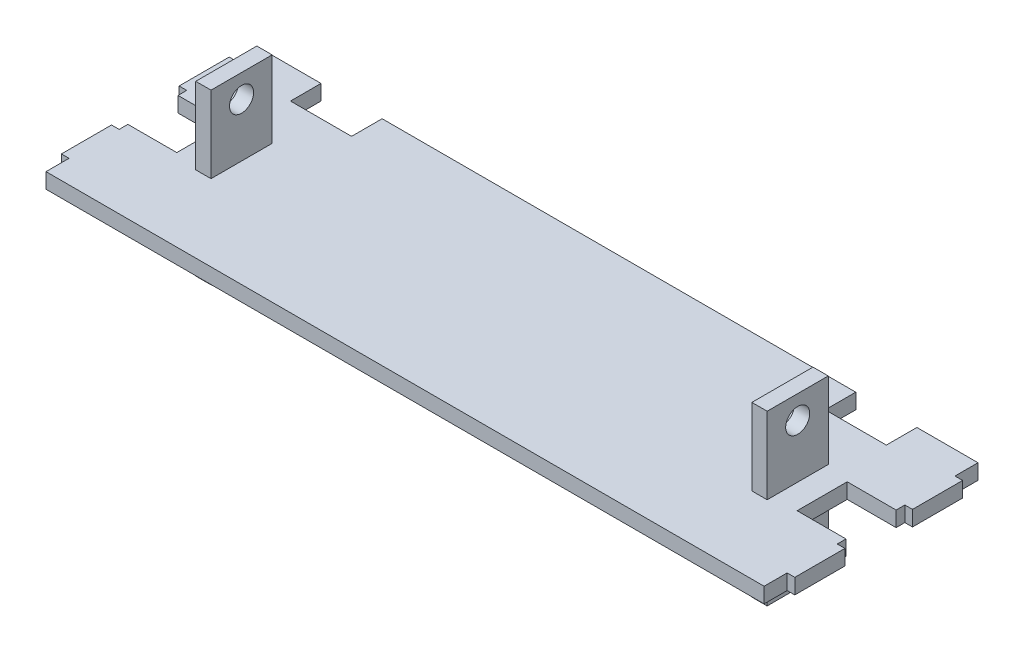
SolidWorks part; units mm, degrees
ref_plane "Front Plane" through (0, 0, 0) normal (0, 0, 1) x (1, 0, 0)
ref_plane "Top Plane" through (0, 0, 0) normal (0, 1, 0) x (1, 0, 0)
ref_plane "Right Plane" through (0, 0, 0) normal (1, 0, 0) x (0, 0, -1)
sketch "Sketch1" plane through (0, 0, 0) normal (0, 1, 0) x (1, 0, 0)
  line L0 (0, 72.39) -> (0, -44.45) construction
  line L1 (149.225, -44.45) -> (-149.225, -44.45)
  line L2 (149.225, -44.45) -> (149.225, -34.8747)
  line L3 (149.225, 44.45) -> (123.825, 44.45)
  line L4 (-149.225, -44.45) -> (-149.225, -34.8747)
  line L5 (149.225, -44.45) -> (-149.225, 44.45) construction
  line L6 (149.225, 44.45) -> (-149.225, -44.45) construction
  line L7 (149.225, 10.414) -> (128.905, 10.414)
  line L9 (149.225, -10.414) -> (128.905, -10.414)
  line L10 (128.905, 10.414) -> (128.905, -10.414)
  line L11 (-123.825, 44.45) -> (-149.225, 44.45)
  line L13 (-149.225, -10.414) -> (-128.905, -10.414)
  line L14 (-128.905, 10.414) -> (-128.905, -10.414)
  line L15 (-149.225, 10.414) -> (-128.905, 10.414)
  line L17 (-127, 0) -> (127, 0) construction
  line L18 (-149.225, 14.0467) -> (-152.4, 14.0467)
  line L20 (-149.225, 34.8747) -> (-152.4, 34.8747)
  line L21 (-152.4, 14.0467) -> (-152.4, 34.8747)
  line L22 (-149.225, -34.8747) -> (-152.4, -34.8747)
  line L23 (-152.4, -14.0467) -> (-152.4, -34.8747)
  line L24 (-149.225, -14.0467) -> (-152.4, -14.0467)
  line L27 (149.225, -14.0467) -> (152.4, -14.0467)
  line L28 (152.4, -14.0467) -> (152.4, -34.8747)
  line L29 (149.225, -34.8747) -> (152.4, -34.8747)
  line L30 (149.225, 34.8747) -> (152.4, 34.8747)
  line L31 (152.4, 14.0467) -> (152.4, 34.8747)
  line L32 (149.225, 14.0467) -> (152.4, 14.0467)
  line L34 (-149.225, 34.8747) -> (-149.225, 44.45)
  line L35 (-149.225, -14.0467) -> (-149.225, -10.414)
  line L36 (149.225, 34.8747) -> (149.225, 44.45)
  line L37 (149.225, -14.0467) -> (149.225, -10.414)
  line L38 (-149.225, 10.414) -> (-149.225, 14.0467)
  line L39 (149.225, 10.414) -> (149.225, 14.0467)
  line L40 (-123.825, 44.45) -> (-123.825, 31.75)
  line L41 (-123.825, 31.75) -> (-98.425, 31.75)
  line L42 (-98.425, 44.45) -> (-98.425, 31.75)
  line L44 (98.425, 44.45) -> (98.425, 31.75)
  line L45 (98.425, 31.75) -> (123.825, 31.75)
  line L46 (123.825, 44.45) -> (123.825, 31.75)
  line L47 (98.425, 44.45) -> (-98.425, 44.45)
  point P0 (0, 0)
  point P6 (127, 0)
  dimension "D1" = 298.45
  dimension "D2" = 88.9
  dimension "D3" = 20.828
  dimension "D5" = 3.175
  dimension "D6" = 20.828
  dimension "D4" = 20.32
  dimension "D7" = 12.7
  dimension "D8" = 25.4
  dimension "D9" = 25.4
  dimension "D10" = 12.7
  dimension "D12" = 25.4
  dimension "D11" = 25.4
  dimension "D13" = 304.8
  dimension "D14" = 14.0467
  dimension "D15" = 10.414
extrude "Boss-Extrude1" add sketch "Sketch1" along normal mid plane 6.35
sketch "Sketch2" plane through (0, 0, 0) normal (0, 1, 0) x (1, 0, 0)
  line L1 (112.395, -12.7) -> (118.745, -12.7)
  line L2 (112.395, -12.7) -> (112.395, 12.7)
  line L3 (112.395, 12.7) -> (118.745, 12.7)
  line L4 (118.745, -12.7) -> (118.745, 12.7)
  line L5 (112.395, -12.7) -> (118.745, 12.7) construction
  line L6 (112.395, 12.7) -> (118.745, -12.7) construction
  line L7 (0, 44.45) -> (0, -44.45) construction
  line L8 (98.425, 44.45) -> (-98.425, 44.45) construction
  line L13 (128.905, -10.414) -> (128.905, 10.414) construction
  line L14 (-149.225, -44.45) -> (149.225, -44.45) construction
  line L15 (-112.395, -12.7) -> (-112.395, 12.7)
  line L16 (-112.395, -12.7) -> (-118.745, -12.7)
  line L17 (-118.745, -12.7) -> (-118.745, 12.7)
  line L18 (-112.395, 12.7) -> (-118.745, 12.7)
  point P0 (115.57, 0)
  point P10 (128.905, 0)
  dimension "D2" = 10.16
  dimension "D4" = 25.4
  dimension "D5" = 6.35
extrude "Boss-Extrude2" add sketch "Sketch2" along normal mid plane 70.104
sketch "Sketch5" plane through (-118.745, 0, 0) normal (-1, 0, 0) x (0, 0, 1)
  line L0 (0, 25.4) -> (0, -25.4) construction
  line L1 (-44.45, 0) -> (44.45, 0) construction
  line L2 (-44.45, 3.175) -> (-44.45, -3.175) construction
  line L3 (44.45, 3.175) -> (44.45, -3.175) construction
  circle A0 centre (0, 25.4) radius 5.0038
  circle A1 centre (0, -25.4) radius 5.0038
  dimension "D2" = 10.0076
  dimension "D1" = 25.4
extrude "Cut-Extrude1" cut sketch "Sketch5" against normal through all both and the other way through all
equation "\"length\"= \"Avionics_Board_Length\""
equation "\"width\"=3.5"
equation "\"height\"= 0.25"
equation "\"D2@Sketch1\"=\"width\""
equation "\"eyebolt width\"= 0.82"
equation "\"eyebolt length\"= 0.8"
equation "\"D3@Sketch1\"=\"eyebolt width\""
equation "\"D4@Sketch1\"=\"eyebolt length\""
equation "\"lead screw holder height\"= 2.76"
equation "\"lead screw diameter\"=0.394"
equation "\"distance from holders to board\"=0.4"
equation "\"D2@Sketch5\"=\"lead screw diameter\""
equation "\"Mid_Coupler_Length\" = 12in"
equation "\"Avionics_Bulkhead_Thickness\" = 0.25in"
equation "\"Avionics_Bulkhead_Lip\" = 0.125in"
equation "\"Avionics_Board_Length\" = \"Mid_Coupler_Length\" - 2*\"Avionics_Bulkhead_Lip\""
equation "\"Body_Tube_OD\"= 4.024in"
equation "\"D1@Sketch1\"=\"length\""
equation "\"Lead_Screw_Dist\" = 2in"
equation "\"D1@Sketch5\"=\"Lead_Screw_Dist\"/2"
